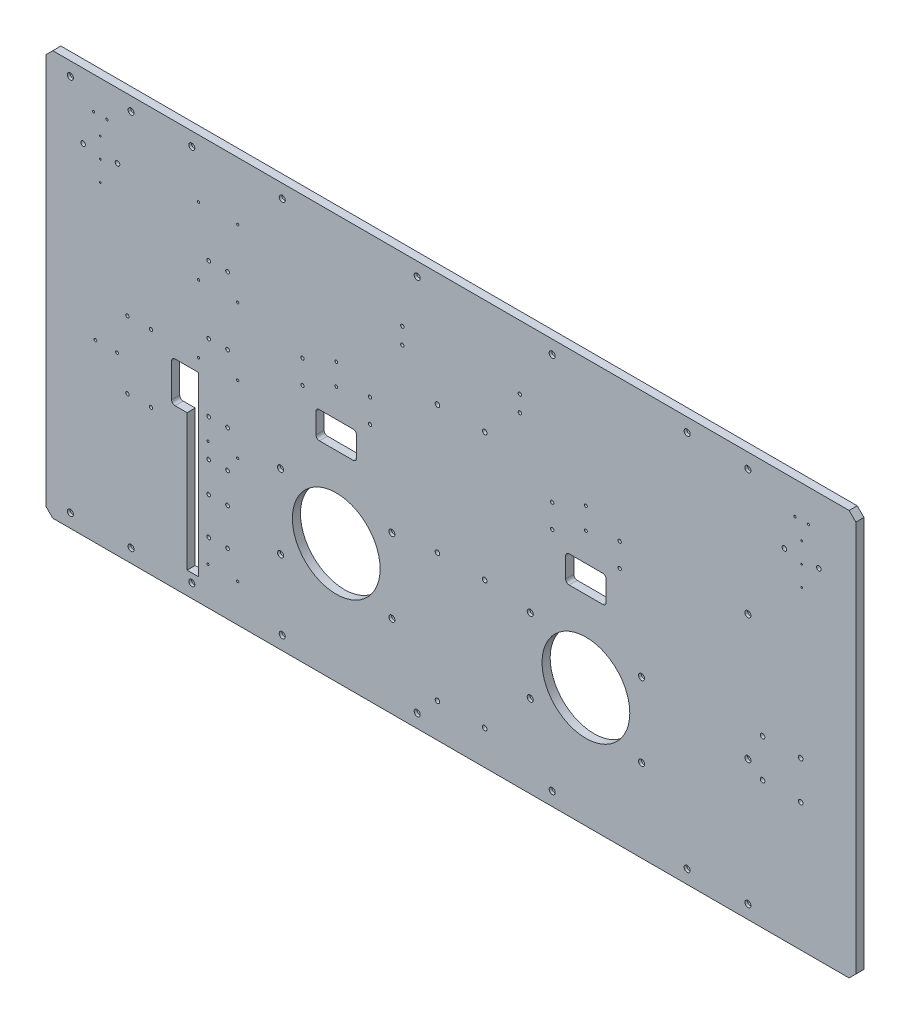
SolidWorks part; units mm, degrees
ref_plane "Front Plane" through (0, 0, 0) normal (0, 0, 1) x (1, 0, 0)
ref_plane "Top Plane" through (0, 0, 0) normal (0, 1, 0) x (1, 0, 0)
ref_plane "Right Plane" through (0, 0, 0) normal (1, 0, 0) x (0, 0, -1)
sketch "Sketch1" plane through (0, 0, 0) normal (0, 0, 1) x (1, 0, 0)
  line L0 (-600, 290) -> (-590, 300)
  line L1 (-590, -300) -> (590, -300)
  line L2 (-600, -290) -> (-600, 290)
  line L3 (-590, 300) -> (590, 300)
  line L4 (600, -290) -> (600, 290)
  line L5 (-600, -300) -> (600, 300) construction
  line L6 (-600, 300) -> (600, -300) construction
  line L7 (-600, -290) -> (-590, -300)
  line L8 (590, 300) -> (600, 290)
  line L9 (590, -300) -> (600, -290)
  point P0 (0, 0)
  dimension "D1" = 1200
  dimension "D2" = 600
extrude "Boss-Extrude1" add sketch "Sketch1" along normal mid plane 12
sketch "Sketch2" plane through (0, 0, 6) normal (0, 0, 1) x (1, 0, 0)
  line L0 (-327, 230) -> (-377, 230) construction
  line L1 (-377, 230) -> (-327, 230) construction
  line L2 (-324, 227) -> (-324, 218.5) construction
  line L3 (-324, 230) -> (-304, 230)
  line L4 (-324, 230) -> (-324, -15)
  line L5 (-319, -20) -> (-304, -20)
  line L6 (-304, 230) -> (-304, -20)
  line L7 (-324, 210.5) -> (-324, 218.5) construction
  line L8 (-324, 227) -> (-324, -15) construction
  line L9 (-313, -20) -> (-319, -20) construction
  line L15 (255, 36.9) -> (145, 36.9) construction
  line L16 (175, 36.9) -> (225, 36.9)
  line L28 (0, 300) -> (0, -35) construction
  line L30 (-413.9, 21.1) -> (-413.9, -88.9) construction
  line L31 (-408.9, -5) -> (-385, -5)
  line L32 (-413.9, -10) -> (-413.9, -60)
  line L33 (-408.9, -65) -> (-385, -65)
  line L34 (-380, -10) -> (-380, -60)
  line L35 (-380, -237) -> (-380, 227) construction
  line L39 (170, 31.9) -> (170, 1.9)
  line L40 (175, -3.1) -> (225, -3.1)
  line L41 (230, 31.9) -> (230, 1.9)
  line L42 (200, -3.1) -> (200, 36.9) construction
  line L43 (135, -122.5) -> (-105, -122.5) construction
  line L44 (15, -122.5) -> (15, -63.9) construction
  line L45 (-170, -3.1) -> (-170, 36.9) construction
  line L46 (-200, 31.9) -> (-200, 1.9)
  line L47 (-145, -3.1) -> (-195, -3.1)
  line L48 (-140, 31.9) -> (-140, 1.9)
  line L49 (-145, 36.9) -> (-195, 36.9)
  line L50 (590, 300) -> (-590, 300) construction
  line L51 (-380, -35) -> (-413.9, -35) construction
  circle A0 centre (-170, -122.5) radius 65
  circle A1 centre (200, -122.5) radius 65
  arc A2 (-324, -15) -> (-319, -20) centre (-319, -15) ccw
  arc A11 (-385, -5) -> (-380, -10) centre (-385, -10) cw
  arc A12 (-408.9, -5) -> (-413.9, -10) centre (-408.9, -10) ccw
  arc A13 (-413.9, -60) -> (-408.9, -65) centre (-408.9, -60) ccw
  arc A14 (-385, -65) -> (-380, -60) centre (-385, -60) ccw
  circle A23 centre (200, -122.5) radius 17 construction
  arc A24 (225, 36.9) -> (230, 31.9) centre (225, 31.9) cw
  arc A25 (225, -3.1) -> (230, 1.9) centre (225, 1.9) ccw
  arc A26 (170, 1.9) -> (175, -3.1) centre (175, 1.9) ccw
  arc A27 (175, 36.9) -> (170, 31.9) centre (175, 31.9) ccw
  arc A28 (-145, 36.9) -> (-140, 31.9) centre (-145, 31.9) cw
  arc A29 (-140, 1.9) -> (-145, -3.1) centre (-145, 1.9) cw
  arc A30 (-195, -3.1) -> (-200, 1.9) centre (-195, 1.9) cw
  arc A31 (-195, 36.9) -> (-200, 31.9) centre (-195, 31.9) ccw
  point P30 (-324, -20)
  point P39 (230, 36.9)
  point P43 (230, -3.1)
  point P46 (170, -3.1)
  point P71 (-140, -3.1)
  point P72 (-200, -3.1)
  point P73 (-200, 36.9)
  point P91 (-413.9, -5)
  point P94 (-413.9, -65)
  dimension "D1" = 130
  dimension "D2" = 130
  dimension "D4" = 5
  dimension "D8" = 5
  dimension "D11" = 5
  dimension "D3" = 20
  dimension "D5" = 370
  dimension "D6" = 60
  dimension "D7" = 40
  dimension "D9" = 60
  dimension "D10" = 335
extrude "Cut-Extrude1" cut sketch "Sketch2" against normal up to next
sketch "Sketch20" plane through (0, 0, 6) normal (0, 0, 1) x (1, 0, 0)
  line L0 (-304, -20) -> (-304, 230) construction
  line L1 (-304, -20) -> (-304, 230)
  line L2 (-304, 230) -> (-324, 230) construction
  line L3 (-304, 230) -> (-324, 230)
  line L4 (-324, 230) -> (-324, -15) construction
  line L5 (-324, 230) -> (-324, -15)
  line L6 (-319, -20) -> (-304, -20) construction
  line L7 (-319, -20) -> (-304, -20)
  arc A0 (-324, -15) -> (-319, -20) centre (-319, -15) ccw construction
  arc A1 (-324, -15) -> (-319, -20) centre (-319, -15) ccw
extrude "Boss-Extrude2" add sketch "Sketch20" against normal up to surface (12 mm away) up to face at (-396.95, -35, -6)
hole_wizard "M8x1.25 Tapped Hole1" positions "Sketch3" profile "Sketch4" tap size "M8x1.25" standard "JIS" end condition up to next
sketch "Sketch3" plane through (0, 0, 6) normal (0, 0, 1) x (1, 0, 0)
  point P27 (-20, 130.77)
  point P30 (50, 130.77)
  point P33 (50, -59.23)
  point P36 (-20, -59.23)
  point P39 (-20, -249.23)
  point P42 (50, -249.23)
  point P47 (-494.1, 203.3)
  point P49 (-545.1, 203.3)
  point P52 (545.1, 203.3)
  point P54 (494.1, 203.3)
sketch "Sketch4" plane through (-20, 130.77, 6) normal (1, 0, 0) x (0, -1, 0)
  line L0 (0, 0) -> (0, 12)
  line L1 (0, 12) -> (3.4, 12)
  line L2 (3.4, 12) -> (3.4, 0)
  line L5 (3.4, 0) -> (0, 0)
  line L11 (0, -6.35) -> (0, 107.95) construction
  dimension "Thru Tap Drill Dia." = 6.8
  dimension "Thru Tap Drill Depth" = 12
cosmetic thread "Hole Thread1" parameters "D2"=8
cosmetic thread "Hole Thread2" parameters "D2"=8
cosmetic thread "Hole Thread3" parameters "D2"=8
cosmetic thread "Hole Thread4" parameters "D2"=8
cosmetic thread "Hole Thread5" parameters "D2"=8
cosmetic thread "Hole Thread6" parameters "D2"=8
cosmetic thread "Hole Thread31" parameters "D2"=8
cosmetic thread "Hole Thread32" parameters "D2"=8
cosmetic thread "Hole Thread33" parameters "D2"=8
cosmetic thread "Hole Thread34" parameters "D2"=8
hole_wizard "M4x0.7 Tapped Hole1" positions "Sketch7" profile "Sketch8" tap size "M4x0.7" standard "JIS" end condition up to next
sketch "Sketch7" plane through (0, 0, -6) normal (0, 0, -1) x (-1, 0, 0)
  point P41 (-529.6, 251.9)
  point P44 (-509.6, 251.9)
  point P48 (509.6, 251.9)
  point P51 (529.6, 251.9)
  point P56 (316, -244)
  point P59 (360, -244.1)
  point P105 (374, 213.9)
  point P111 (316, 213.9)
  point P119 (316, -86.1)
  point P121 (360, -86.1)
  point P126 (316, 13.9)
  point P128 (374, 13.9)
  point P133 (374, 113.9)
  point P135 (316, 113.9)
sketch "Sketch8" plane through (529.6, 251.9, -6) normal (1, 0, 0) x (0, 1, 0)
  line L0 (0, 0) -> (0, 12)
  line L1 (0, 12) -> (1.65, 12)
  line L2 (1.65, 12) -> (1.65, 0)
  line L5 (1.65, 0) -> (0, 0)
  line L11 (0, -6.35) -> (0, 107.95) construction
  dimension "Thru Tap Drill Dia." = 3.3
  dimension "Thru Tap Drill Depth" = 12
cosmetic thread "Hole Thread11" parameters "D2"=4
cosmetic thread "Hole Thread12" parameters "D2"=4
cosmetic thread "Hole Thread13" parameters "D2"=4
cosmetic thread "Hole Thread14" parameters "D2"=4
cosmetic thread "Hole Thread43" parameters "D2"=4
cosmetic thread "Hole Thread44" parameters "D2"=4
cosmetic thread "Hole Thread45" parameters "D2"=4
cosmetic thread "Hole Thread49" parameters "D2"=4
cosmetic thread "Hole Thread50" parameters "D2"=4
cosmetic thread "Hole Thread51" parameters "D2"=4
cosmetic thread "Hole Thread63" parameters "D2"=4
cosmetic thread "Hole Thread64" parameters "D2"=4
cosmetic thread "Hole Thread65" parameters "D2"=4
cosmetic thread "Hole Thread66" parameters "D2"=4
hole_wizard "M6x1.0 Tapped Hole1" positions "Sketch9" profile "Sketch10" tap size "M6x1.0" standard "JIS" end condition up to next
sketch "Sketch9" plane through (0, 0, -6) normal (0, 0, -1) x (-1, 0, 0)
  circle A0 centre (-200, -122.5) radius 65 construction
  point P0 (-102.1, 205.3)
  point P13 (120, 90.5)
  point P16 (120, 55.5)
  point P19 (220, 90.5)
  point P22 (220, 55.5)
  point P37 (-150, 90.5)
  point P40 (-150, 55.5)
  point P43 (-250, 55.5)
  point P46 (-250, 90.5)
  point P50 (479.4, -85)
  point P53 (479.4, 15)
  point P56 (444.4, 15)
  point P59 (444.4, -85)
  point P75 (72.1, 205.3)
  point P79 (-102.1, 181.3)
  point P82 (72.1, 181.3)
  point P87 (0, 0)
  point P88 (0, 0)
  point P89 (0, 0)
  point P90 (0, 0)
  dimension "D3" = 50
  dimension "D1" = 100
  dimension "D2" = 35
  dimension "D4" = 213
  dimension "D5" = 370
  dimension "D6" = 100
  dimension "D7" = 47.9
  dimension "D8" = 174.2
  dimension "D9" = 114.8
  dimension "D10" = 24
sketch "Sketch10" plane through (102.1, 205.3, -6) normal (1, 0, 0) x (0, 1, 0)
  line L0 (0, 0) -> (0, 12)
  line L1 (0, 12) -> (2.5, 12)
  line L2 (2.5, 12) -> (2.5, 0)
  line L5 (2.5, 0) -> (0, 0)
  line L11 (0, -6.35) -> (0, 107.95) construction
  dimension "Thru Tap Drill Dia." = 5
  dimension "Thru Tap Drill Depth" = 12
cosmetic thread "Hole Thread15" parameters "D2"=6
cosmetic thread "Hole Thread16" parameters "D2"=6
cosmetic thread "Hole Thread17" parameters "D2"=6
cosmetic thread "Hole Thread18" parameters "D2"=6
cosmetic thread "Hole Thread23" parameters "D2"=6
cosmetic thread "Hole Thread24" parameters "D2"=6
cosmetic thread "Hole Thread25" parameters "D2"=6
cosmetic thread "Hole Thread26" parameters "D2"=6
cosmetic thread "Hole Thread52" parameters "D2"=6
cosmetic thread "Hole Thread53" parameters "D2"=6
cosmetic thread "Hole Thread54" parameters "D2"=6
cosmetic thread "Hole Thread55" parameters "D2"=6
cosmetic thread "Hole Thread56" parameters "D2"=6
cosmetic thread "Hole Thread57" parameters "D2"=6
cosmetic thread "Hole Thread58" parameters "D2"=6
cosmetic thread "Hole Thread59" parameters "D2"=6
hole_wizard "CBORE for M8 Pan Head Screw1" positions "Sketch11" profile "Sketch12" counterbore size "M8" standard "JIS" end condition up to next
sketch "Sketch11" plane through (0, 0, -6) normal (0, 0, -1) x (-1, 0, 0)
  point P25 (-282.5, -177.5)
  point P28 (-117.5, -177.5)
  point P31 (-117.5, -67.5)
  point P34 (-282.5, -67.5)
  point P37 (87.5, -67.5)
  point P42 (252.5, -177.5)
  point P45 (252.5, -67.5)
  point P50 (87.5, -177.5)
sketch "Sketch12" plane through (282.5, -177.5, -6) normal (1, 0, 0) x (0, 1, 0)
  line L0 (0, 0) -> (0, 12)
  line L1 (0, 12) -> (4.5, 12)
  line L3 (4.5, 12) -> (4.5, 8)
  line L4 (4.5, 8) -> (7, 8)
  line L5 (7, 8) -> (7, 0)
  line L7 (7, 0) -> (0, 0)
  line L11 (0, -6.35) -> (0, 107.95) construction
  dimension "Thru Hole Dia." = 9
  dimension "Thru Hole Depth" = 12
  dimension "C'Bore Dia." = 14
  dimension "C'Bore Depth" = 8
hole_wizard "CBORE for M5 Pan Head Screw1" positions "Sketch17" profile "Sketch18" counterbore size "M5" standard "JIS" end condition up to next
sketch "Sketch17" plane through (0, 0, -6) normal (0, 0, -1) x (-1, 0, 0)
  point P102 (331, -209.1)
  point P105 (331, -154.1)
  point P113 (331, -54.1)
  point P114 (331, 45.9)
  point P115 (331, 145.9)
  point P122 (359, -209.1)
  point P123 (359, -154.1)
  point P124 (359, -54.1)
  point P125 (359, 45.9)
  point P126 (359, 145.9)
  point P144 (331, -109.1)
  point P146 (359, -109.1)
  dimension "D1" = 4
  dimension "D3" = 2
sketch "Sketch18" plane through (-331, -209.1, -6) normal (1, 0, 0) x (0, 1, 0)
  line L0 (0, 0) -> (0, 12)
  line L1 (0, 12) -> (2.75, 12)
  line L3 (2.75, 12) -> (2.75, 5)
  line L4 (2.75, 5) -> (4.75, 5)
  line L5 (4.75, 5) -> (4.75, 0)
  line L7 (4.75, 0) -> (0, 0)
  line L11 (0, -6.35) -> (0, 107.95) construction
  dimension "Thru Hole Dia." = 5.5
  dimension "Thru Hole Depth" = 12
  dimension "C'Bore Dia." = 9.5
  dimension "C'Bore Depth" = 5
ref_plane "Plane1" through (-371.907, -247.37, 7) normal (1, 0, 0) x (0, 0, -1)
sketch "Sketch19" plane through (0, 0, -6) normal (0, 0, -1) x (-1, 0, 0)
  line L0 (170, -122.5) -> (170, 300) construction
  line L1 (170, 300) -> (-233.1127, 300) construction
  line L2 (-590, 300) -> (590, 300) construction
ref_plane "Plane2" through (-170, 300, -6) normal (1, 0, 0) x (0, 0, -1)
ref_plane "Plane3" through (-345, 300, -6) normal (1, 0, 0) x (0, 0, -1)
sketch "Sketch21" plane through (0, 0, -6) normal (0, 0, -1) x (-1, 0, 0)
  line L1 (391, -267.1) -> (374, -267.1)
  line L2 (391, -267.1) -> (391, -5)
  line L3 (391, -5) -> (374, -5)
  line L4 (374, -267.1) -> (374, -5)
  line L5 (385, -5) -> (408.9, -5) construction
  circle A0 centre (360, -244.1) radius 1.65 construction
  dimension "D1" = 14
  dimension "D2" = 17
  dimension "D3" = 23
extrude "Cut-Extrude2" cut sketch "Sketch21" against normal through all
hole_wizard "CBORE for M8 Socket Head Cap Screw2" positions "Sketch26" profile "Sketch27" counterbore size "M8" standard "JIS" end condition through all
sketch "Sketch26" plane through (0, 0, -6) normal (0, 0, -1) x (-1, 0, 0)
  line L0 (590, -300) -> (-590, -300) construction
  line L2 (600, 290) -> (600, -290) construction
  point P0 (564, -280)
  point P2 (474, -280)
  point P8 (384, -280)
  point P18 (563.0967, -280)
  point P19 (564, -280)
  dimension "D1" = 90
  dimension "D2" = 20
  dimension "D3" = 90
  dimension "D4" = 36
sketch "Sketch27" plane through (-564, -280, -6) normal (1, 0, 0) x (0, 1, 0)
  line L0 (0, 0) -> (0, 12)
  line L1 (0, 12) -> (4.5, 12)
  line L3 (4.5, 12) -> (4.5, 8)
  line L4 (4.5, 8) -> (7.5, 8)
  line L5 (7.5, 8) -> (7.5, 0)
  line L7 (7.5, 0) -> (0, 0)
  line L11 (0, -6.35) -> (0, 107.95) construction
  dimension "Thru Hole Dia." = 9
  dimension "Thru Hole Depth" = 12
  dimension "C'Bore Dia." = 15
  dimension "C'Bore Depth" = 8
pattern_linear "LPattern1" count 2 spacing 560 along (0, 1, 0) of "CBORE for M8 Socket Head Cap Screw2"
hole_wizard "CBORE for M8 Socket Head Cap Screw3" positions "Sketch28" profile "Sketch29" counterbore size "M8" standard "JIS" end condition through all
sketch "Sketch28" plane through (0, 0, -6) normal (0, 0, -1) x (-1, 0, 0)
  line L0 (600, 290) -> (600, -290) construction
  line L1 (590, -300) -> (-590, -300) construction
  point P0 (250, -280)
  point P5 (0, 0)
  dimension "D1" = 350
  dimension "D2" = 20
sketch "Sketch29" plane through (-250, -280, -6) normal (1, 0, 0) x (0, 1, 0)
  line L0 (0, 0) -> (0, 12)
  line L1 (0, 12) -> (4.5, 12)
  line L3 (4.5, 12) -> (4.5, 8)
  line L4 (4.5, 8) -> (7.5, 8)
  line L5 (7.5, 8) -> (7.5, 0)
  line L7 (7.5, 0) -> (0, 0)
  line L11 (0, -6.35) -> (0, 107.95) construction
  dimension "Thru Hole Dia." = 9
  dimension "Thru Hole Depth" = 12
  dimension "C'Bore Dia." = 15
  dimension "C'Bore Depth" = 8
pattern_linear "LPattern2" count 4 spacing 200 along (1, 0, 0) of "CBORE for M8 Socket Head Cap Screw3"
mirror "Mirror1" about plane through (0, 0, 0) normal (0, 1, 0) of "LPattern2", "CBORE for M8 Socket Head Cap Screw3"
hole_wizard "CBORE for M8 Socket Head Cap Screw4" positions "Sketch32" profile "Sketch33" counterbore size "M8" standard "JIS" end condition through all
sketch "Sketch32" plane through (0, 0, -6) normal (0, 0, -1) x (-1, 0, 0)
  line L0 (600, 290) -> (600, -290) construction
  line L1 (590, -300) -> (-590, -300) construction
  point P0 (-440, -280)
  dimension "D1" = 1040
  dimension "D2" = 20
sketch "Sketch33" plane through (440, -280, -6) normal (1, 0, 0) x (0, 1, 0)
  line L0 (0, 0) -> (0, 12)
  line L1 (0, 12) -> (4.5, 12)
  line L3 (4.5, 12) -> (4.5, 8)
  line L4 (4.5, 8) -> (7.5, 8)
  line L5 (7.5, 8) -> (7.5, 0)
  line L7 (7.5, 0) -> (0, 0)
  line L11 (0, -6.35) -> (0, 107.95) construction
  dimension "Thru Hole Dia." = 9
  dimension "Thru Hole Depth" = 12
  dimension "C'Bore Dia." = 15
  dimension "C'Bore Depth" = 8
pattern_linear "LPattern3" count 4 spacing 186 along (0, 1, 0) of "CBORE for M8 Socket Head Cap Screw4"
hole_wizard "M3x0.5 Tapped Hole1" positions "Sketch36" profile "Sketch35" tap size "M3x0.5" standard "JIS" end condition through all
sketch "Sketch36" plane through (0, 0, -6) normal (0, 0, -1) x (-1, 0, 0)
  circle A0 centre (-529.6, 251.9) radius 1.65 construction
  circle A1 centre (509.6, 251.9) radius 1.65 construction
  point P0 (519.6, 225.9)
  point P5 (-519.6, 225.9)
  point P13 (0, 0)
  dimension "D1" = 10
  dimension "D2" = 26
  dimension "D3" = 10
sketch "Sketch35" plane through (-519.6, 225.9, -6) normal (1, 0, 0) x (0, 1, 0)
  line L0 (0, 0) -> (0, 12)
  line L1 (0, 12) -> (1.25, 12)
  line L2 (1.25, 12) -> (1.25, 0)
  line L5 (1.25, 0) -> (0, 0)
  line L11 (0, -6.35) -> (0, 107.95) construction
  dimension "Thru Tap Drill Dia." = 2.5
  dimension "Thru Tap Drill Depth" = 12
cosmetic thread "Hole Thread67" parameters "D2"=3
cosmetic thread "Hole Thread68" parameters "D2"=3
pattern_linear "LPattern4" count 3 spacing 30 along (0, -1, 0) of "M3x0.5 Tapped Hole1"
hole_wizard "M5x0.8 Tapped Hole1" positions "Sketch39" profile "Sketch40" tap size "M5x0.8" standard "JIS" end condition through all
sketch "Sketch39" plane through (0, 0, -6) normal (0, 0, -1) x (-1, 0, 0)
  circle A0 centre (359, 45.9) radius 4.75 construction
  circle A1 centre (120, 90.5) radius 2.5 construction
  circle A2 centre (-250, 90.5) radius 2.5 construction
  point P0 (494.8435, -39.8599)
  point P2 (526.8435, -39.8599)
  point P7 (-200, 111)
  point P9 (-200, 79)
  point P11 (170, 111)
  point P13 (170, 79)
  point P23 (0, 0)
  point P26 (0, 0)
  point P29 (0, 0)
  dimension "D3" = 85.7599
  dimension "D4" = 50
  dimension "D5" = 20.5
  dimension "D7" = 50
  dimension "D9" = 20.5
  dimension "D1" = 135.8435
  dimension "D2" = 32
  dimension "D6" = 32
  dimension "D8" = 32
sketch "Sketch40" plane through (-494.8435, -39.8599, -6) normal (1, 0, 0) x (0, 1, 0)
  line L0 (0, 0) -> (0, 12)
  line L1 (0, 12) -> (2.1, 12)
  line L2 (2.1, 12) -> (2.1, 0)
  line L5 (2.1, 0) -> (0, 0)
  line L11 (0, -6.35) -> (0, 107.95) construction
  dimension "Thru Tap Drill Dia." = 4.2
  dimension "Thru Tap Drill Depth" = 12
cosmetic thread "Hole Thread69" parameters "D2"=5
cosmetic thread "Hole Thread70" parameters "D2"=5
cosmetic thread "Hole Thread71" parameters "D2"=5
cosmetic thread "Hole Thread72" parameters "D2"=5
cosmetic thread "Hole Thread73" parameters "D2"=5
cosmetic thread "Hole Thread74" parameters "D2"=5
hole_wizard "M8x1.25 Tapped Hole2" positions "Sketch44" profile "Sketch42" tap size "M8x1.25" standard "JIS" end condition through all
sketch "Sketch44" plane through (0, 0, -6) normal (0, 0, -1) x (-1, 0, 0)
  line L1 (-518.2843, -53.7157) -> (-461.7157, -110.2843) construction
  line L3 (590, -300) -> (-590, -300) construction
  line L4 (-600, -290) -> (-600, 290) construction
  line L5 (-461.7157, -53.7157) -> (-518.2843, -110.2843) construction
  circle A0 centre (-490, -82) radius 40 construction
  point P0 (-518.2843, -110.2843)
  point P2 (-461.7157, -53.7157)
  point P4 (-461.7157, -110.2843)
  point P6 (-518.2843, -53.7157)
  point P33 (0, 0)
  point P34 (0, 0)
  point P35 (0, 0)
  dimension "D1" = 90
  dimension "D2" = 218
  dimension "D5" = 80
  dimension "D3" = 110
  dimension "D4" = 45
sketch "Sketch42" plane through (518.2843, -110.2843, -6) normal (1, 0, 0) x (0, 1, 0)
  line L0 (0, 0) -> (0, 12)
  line L1 (0, 12) -> (3.4, 12)
  line L2 (3.4, 12) -> (3.4, 0)
  line L5 (3.4, 0) -> (0, 0)
  line L11 (0, -6.35) -> (0, 107.95) construction
  dimension "Thru Tap Drill Dia." = 6.8
  dimension "Thru Tap Drill Depth" = 12
cosmetic thread "Hole Thread75" parameters "D2"=8
cosmetic thread "Hole Thread76" parameters "D2"=8
cosmetic thread "Hole Thread77" parameters "D2"=8
cosmetic thread "Hole Thread78" parameters "D2"=8
sketch "Sketch45" plane through (0, 0, -6) normal (0, 0, -1) x (-1, 0, 0)
  line L0 (-136.3508, -288.3099) -> (36.4651, -288.3099) construction
  text T0 "TGM-03-145B-01" font "Century Gothic" height in points 50
  point P2 (36.4651, -288.3099)
extrude "Cut-Extrude3" cut sketch "Sketch45" against normal blind 0.01
